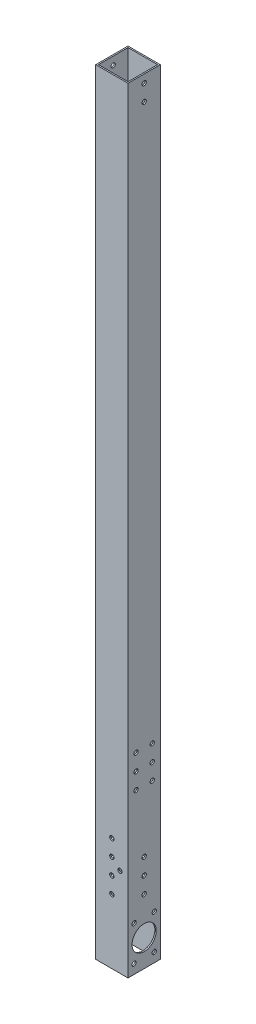
SolidWorks part; units mm, degrees
material "6061-T6 (SS)"
ref_plane "Front Plane" through (0, 0, 0) normal (0, 0, 1) x (1, 0, 0)
ref_plane "Top Plane" through (0, 0, 0) normal (0, 1, 0) x (1, 0, 0)
ref_plane "Right Plane" through (0, 0, 0) normal (1, 0, 0) x (0, 0, -1)
sketch "Sketch1" plane through (0, 0, 0) normal (0, 1, 0) x (1, 0, 0)
  line L0 (17.4625, 17.4625) -> (-17.4625, 17.4625)
  line L1 (19.05, -19.05) -> (-19.05, -19.05)
  line L2 (19.05, -19.05) -> (19.05, 19.05)
  line L3 (19.05, 19.05) -> (-19.05, 19.05)
  line L4 (-19.05, -19.05) -> (-19.05, 19.05)
  line L5 (19.05, -19.05) -> (-19.05, 19.05) construction
  line L6 (19.05, 19.05) -> (-19.05, -19.05) construction
  line L7 (-17.4625, -17.4625) -> (-17.4625, 17.4625)
  line L8 (17.4625, -17.4625) -> (-17.4625, -17.4625)
  line L9 (17.4625, -17.4625) -> (17.4625, 17.4625)
  point P0 (0, 0)
  dimension "D1" = 38.1
  dimension "D2" = 1.5875
extrude "Boss-Extrude1" add sketch "Sketch1" along normal blind 914.4
sketch "Sketch2" plane through (0, 0, 19.05) normal (0, 0, 1) x (1, 0, 0)
  line L1 (-19.05, 0) -> (19.05, 0) construction
  line L2 (0, 114.3) -> (9.525, 104.775) construction
  line L3 (9.525, 104.775) -> (0, 95.25) construction
  circle A0 centre (0, 76.2) radius 2.5527
  circle A1 centre (0, 95.25) radius 2.5527
  circle A4 centre (0, 114.3) radius 2.5527
  circle A5 centre (0, 133.35) radius 2.5527
  circle A7 centre (9.525, 104.775) radius 2.5527
  point P16 (0, 0)
  dimension "D4" = 19.05
  dimension "D5" = 76.2
  dimension "D6" = 19.05
  dimension "D7" = 19.05
  dimension "D8" = 9.525
extrude "Cut-Extrude1" cut sketch "Sketch2" against normal through all
sketch "Sketch3" plane through (19.05, 0, 0) normal (1, 0, 0) x (0, 0, -1)
  line L0 (-19.05, 0) -> (19.05, 0) construction
  line L1 (9.525, 206.375) -> (19.05, 206.375) construction
  line L2 (19.05, 914.4) -> (19.05, 0) construction
  line L3 (-9.525, 206.375) -> (-19.05, 206.375) construction
  line L4 (-19.05, 914.4) -> (-19.05, 0) construction
  line L5 (-19.05, 914.4) -> (19.05, 914.4) construction
  circle A0 centre (0, 76.2) radius 2.5527
  circle A1 centre (0, 95.25) radius 2.5527
  circle A2 centre (0, 114.3) radius 2.5527
  circle A3 centre (-9.525, 225.425) radius 2.5527
  circle A4 centre (-9.525, 206.375) radius 2.5527
  circle A5 centre (-9.525, 187.325) radius 2.5527
  circle A6 centre (9.525, 187.325) radius 2.5527
  circle A7 centre (9.525, 206.375) radius 2.5527
  circle A8 centre (9.525, 225.425) radius 2.5527
  circle A9 centre (0, 904.875) radius 2.5527
  circle A10 centre (0, 885.825) radius 2.5527
  point P10 (0, 0)
  dimension "D1" = 19.05
  dimension "D2" = 19.05
  dimension "D3" = 19.05
  dimension "D4" = 5.1054
  dimension "D5" = 5.1054
  dimension "D7" = 19.05
  dimension "D8" = 19.05
  dimension "D10" = 9.525
  dimension "D6" = 19.05
  dimension "D9" = 206.375
extrude "Cut-Extrude2" cut sketch "Sketch3" against normal through all
sketch "Sketch4" plane through (19.05, 0, 0) normal (1, 0, 0) x (0, 0, -1)
  line L0 (-19.05, 0) -> (19.05, 0) construction
  circle A0 centre (0, 31.75) radius 14.2875
  circle A1 centre (-11.9063, 52.3722) radius 2.5527
  circle A2 centre (11.9063, 52.3722) radius 2.5527
  circle A3 centre (11.9063, 11.1278) radius 2.5527
  circle A4 centre (-11.9063, 11.1278) radius 2.5527
  circle A5 centre (0, 31.75) radius 23.8125 construction
  point P16 (0, 0)
  dimension "D1" = 5.1054
  dimension "D2" = 47.625
  dimension "D3" = 60
  dimension "D4" = 31.75
  dimension "D5" = 28.575
extrude "Cut-Extrude3" cut sketch "Sketch4" against normal through all
